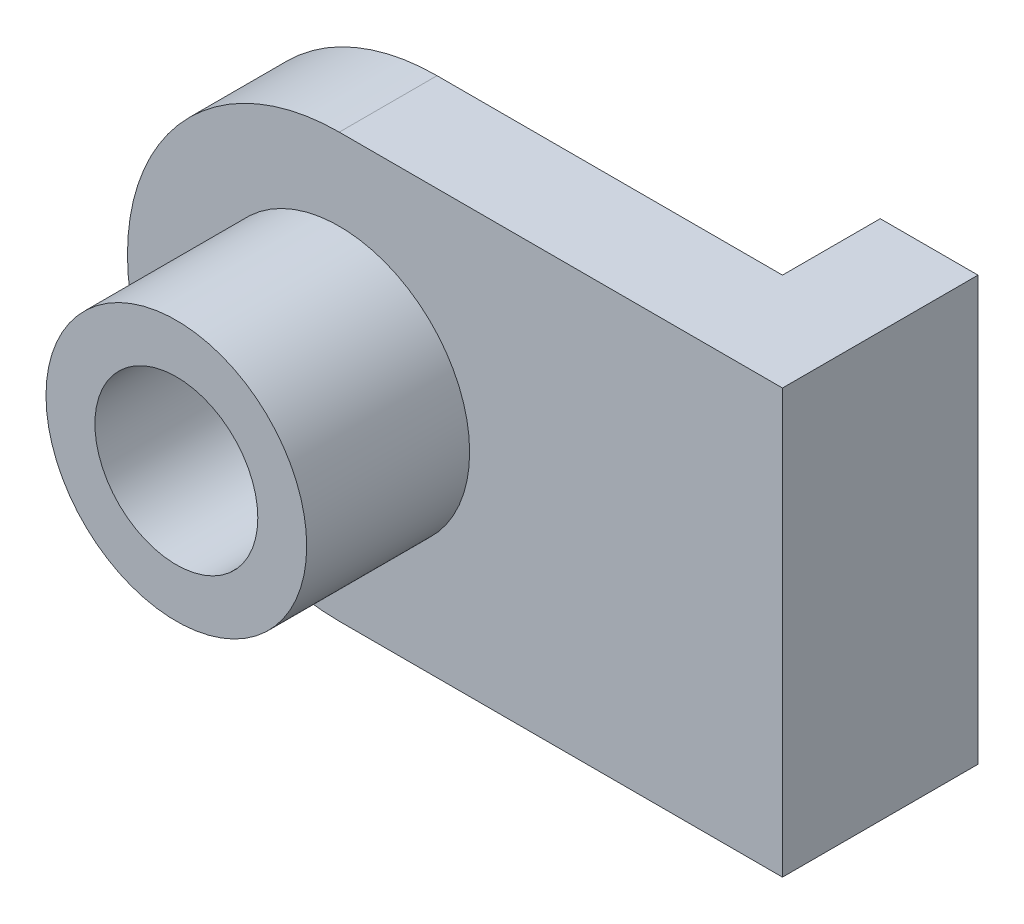
SolidWorks part; units mm, degrees
ref_plane "Front Plane" through (0, 0, 0) normal (0, 0, 1) x (1, 0, 0)
ref_plane "Top Plane" through (0, 0, 0) normal (0, 1, 0) x (1, 0, 0)
ref_plane "Right Plane" through (0, 0, 0) normal (1, 0, 0) x (0, 0, -1)
sketch "Sketch1" plane through (0, 0, 0) normal (0, 0, 1) x (1, 0, 0)
  line L0 (0, 0) -> (68, 0)
  line L1 (68, 0) -> (68, 65)
  line L2 (68, 65) -> (0, 65)
  arc A0 (0, 65) -> (0, 0) centre (0, 32.5) ccw
  dimension "D1" = 65
  dimension "D2" = 68
extrude "Boss-Extrude1" add sketch "Sketch1" along normal blind 15
sketch "Sketch2" plane through (0, 0, 15) normal (0, 0, 1) x (1, 0, 0)
  circle A0 centre (0, 32.5) radius 20
  dimension "D1" = 40
extrude "Boss-Extrude2" add sketch "Sketch2" along normal blind 25
sketch "Sketch3" plane through (0, 0, 40) normal (0, 0, 1) x (1, 0, 0)
  circle A0 centre (0, 32.5) radius 12.5
  dimension "D1" = 25
extrude "Cut-Extrude1" cut sketch "Sketch3" against normal through all
sketch "Sketch4" plane through (0, 0, 0) normal (0, 0, -1) x (-1, 0, 0)
  line L0 (-68, 65) -> (-53, 65)
  line L1 (-68, 65) -> (0, 65) construction
  line L2 (-68, 0) -> (-68, 65) construction
  line L3 (-53, 65) -> (-53, 0)
  line L4 (0, 0) -> (-68, 0) construction
  line L5 (-53, 0) -> (-68, 0)
  line L6 (-68, 0) -> (-68, 65)
  dimension "D1" = 15
extrude "Boss-Extrude3" add sketch "Sketch4" along normal blind 15 contours L5 L6 L0 L3
